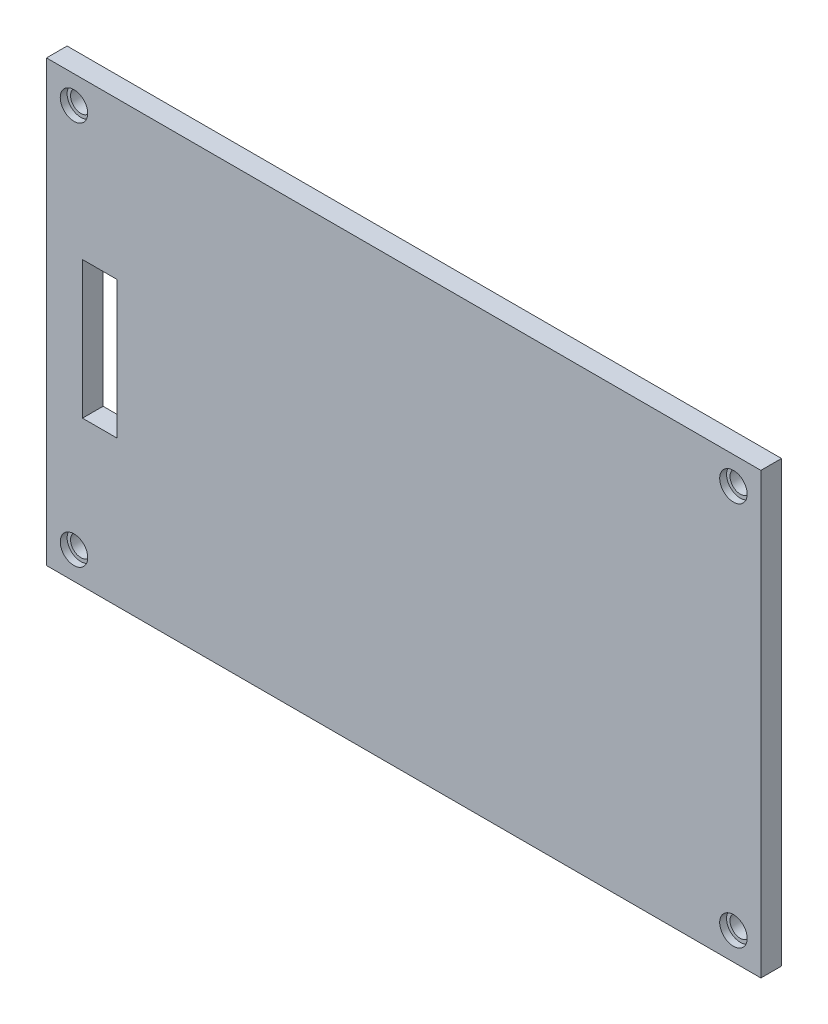
SolidWorks part; units mm, degrees
ref_plane "前视基准面" through (0, 0, 0) normal (0, 0, 1) x (1, 0, 0)
ref_plane "上视基准面" through (0, 0, 0) normal (0, 1, 0) x (1, 0, 0)
ref_plane "右视基准面" through (0, 0, 0) normal (1, 0, 0) x (0, 0, -1)
sketch "草图1" plane through (0, 0, 0) normal (0, 0, 1) x (1, 0, 0)
  line L1 (52, -32) -> (-52, -32)
  line L2 (52, -32) -> (52, 32)
  line L3 (52, 32) -> (-52, 32)
  line L4 (-52, -32) -> (-52, 32)
  line L5 (52, -32) -> (-52, 32) construction
  line L6 (52, 32) -> (-52, -32) construction
  point P0 (0, 0)
  dimension "D1" = 64
  dimension "D2" = 104
extrude "凸台-拉伸1" add sketch "草图1" along normal blind 3
sketch "草图2" plane through (0, 0, 3) normal (0, 0, 1) x (1, 0, 0)
  line L2 (0, 0) -> (0, 50000) construction
  line L3 (0, 0) -> (-50000, 0) construction
  circle A1 centre (-48, 28) radius 1.5
  circle A2 centre (48, 28) radius 1.5
  circle A3 centre (48, -28) radius 1.5
  circle A4 centre (-48, -28) radius 1.5
  dimension "D3" = 3
extrude "切除-拉伸1" cut sketch "草图2" against normal through all
sketch "草图3" plane through (0, 0, 0) normal (0, 0, -1) x (-1, 0, 0)
  line L0 (0, 0) -> (0, 50000) construction
  line L2 (41.7601, -10.8) -> (46.7601, -10.8)
  line L3 (41.7601, -10.8) -> (41.7601, 9.2)
  line L4 (41.7601, 9.2) -> (46.7601, 9.2)
  line L5 (46.7601, -10.8) -> (46.7601, 9.2)
  line L6 (41.7601, -10.8) -> (46.7601, 9.2) construction
  line L7 (41.7601, 9.2) -> (46.7601, -10.8) construction
  point P3 (44.2601, -0.8)
  dimension "D1" = 20
  dimension "D2" = 5
extrude "切除-拉伸2" cut sketch "草图3" against normal through all
sketch "草图4" plane through (0, 0, 3) normal (0, 0, 1) x (1, 0, 0)
  line L0 (0, 0) -> (0, 50000) construction
  line L1 (0, 0) -> (50000, 0) construction
  circle A0 centre (48, 28) radius 2
  circle A1 centre (-48, 28) radius 2
  circle A2 centre (-48, -28) radius 2
  circle A3 centre (48, -28) radius 2
  dimension "D1" = 4
extrude "切除-拉伸3" cut sketch "草图4" against normal blind 1
